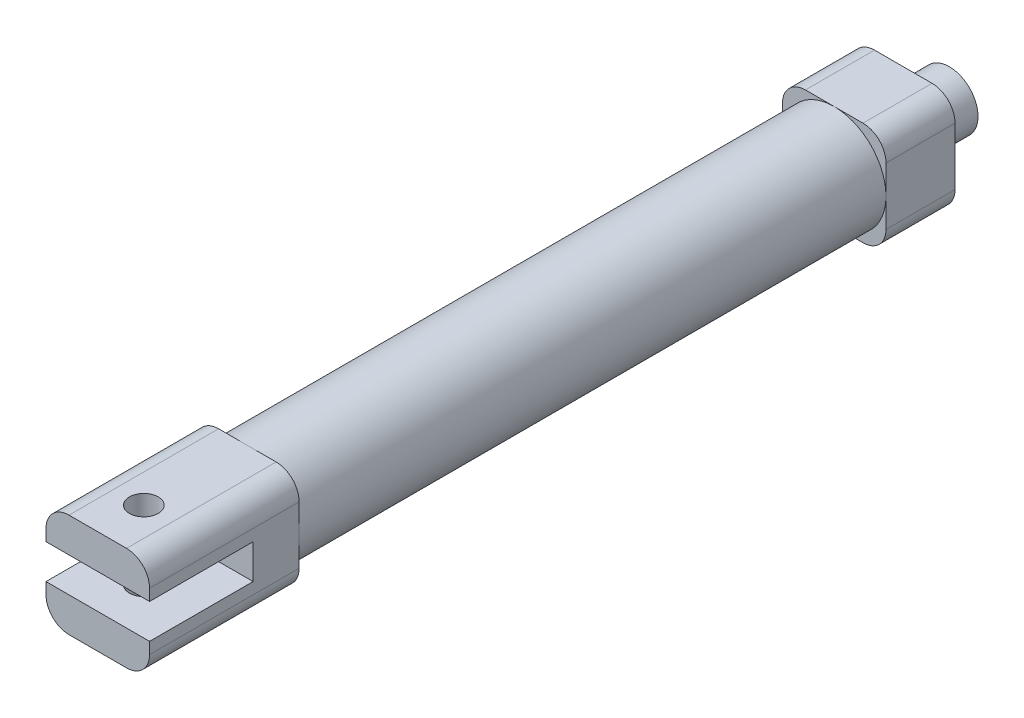
SolidWorks part; units mm, degrees
ref_plane "前视基准面" through (0, 0, 0) normal (0, 0, 1) x (1, 0, 0)
ref_plane "上视基准面" through (0, 0, 0) normal (0, 1, 0) x (1, 0, 0)
ref_plane "右视基准面" through (0, 0, 0) normal (1, 0, 0) x (0, 0, -1)
sketch "草图1" plane through (0, 0, 0) normal (0, 0, 1) x (1, 0, 0)
  circle A0 centre (0, 0) radius 9
  circle A1 centre (0, 0) radius 8
  dimension "D1" = 18
  dimension "D2" = 16
extrude "凸台-拉伸1" add sketch "草图1" along normal blind 102
sketch "草图2" plane through (0, 0, 102) normal (0, 0, 1) x (1, 0, 0)
  line L1 (-5, -9) -> (5, -9)
  line L2 (-9, -5) -> (-9, 5)
  line L3 (-5, 9) -> (5, 9)
  line L4 (9, -5) -> (9, 5)
  line L5 (-9, -9) -> (9, 9) construction
  line L6 (-9, 9) -> (9, -9) construction
  arc A0 (-5, 9) -> (-9, 5) centre (-5, 5) ccw
  arc A1 (9, 5) -> (5, 9) centre (5, 5) ccw
  arc A2 (9, -5) -> (5, -9) centre (5, -5) cw
  arc A3 (-9, -5) -> (-5, -9) centre (-5, -5) ccw
  point P0 (0, 0)
  dimension "D3" = 4
  dimension "D4" = 4
  dimension "D5" = 4
  dimension "D6" = 4
  dimension "D1" = 18
  dimension "D2" = 18
extrude "凸台-拉伸2" add sketch "草图2" along normal blind 26
sketch "草图3" plane through (0, 0, 0) normal (0, 0, -1) x (-1, 0, 0)
  line L1 (-5, -9) -> (5, -9)
  line L2 (-9, -5) -> (-9, 5)
  line L3 (-5, 9) -> (5, 9)
  line L4 (9, -5) -> (9, 5)
  line L5 (-9, -9) -> (9, 9) construction
  line L6 (-9, 9) -> (9, -9) construction
  arc A0 (-9, -5) -> (-5, -9) centre (-5, -5) ccw
  arc A1 (5, -9) -> (9, -5) centre (5, -5) ccw
  arc A2 (9, 5) -> (5, 9) centre (5, 5) ccw
  arc A3 (-5, 9) -> (-9, 5) centre (-5, 5) ccw
  point P0 (0, 0)
  dimension "D3" = 4
  dimension "D1" = 18
  dimension "D2" = 18
extrude "凸台-拉伸3" add sketch "草图3" along normal blind 12
sketch "草图4" plane through (0, 0, -12) normal (0, 0, -1) x (-1, 0, 0)
  circle A0 centre (0, 0) radius 5
extrude "凸台-拉伸4" add sketch "草图4" along normal blind 8
sketch "草图5" plane through (0, 0, -20) normal (0, 0, -1) x (-1, 0, 0)
  circle A0 centre (0, 0) radius 2.5
extrude "切除-拉伸1" cut sketch "草图5" against normal blind 38
sketch "草图6" plane through (-9, 0, 0) normal (-1, 0, 0) x (0, 0, 1)
  line L0 (0, -9) -> (0, 9) construction
  circle A0 centre (-4, 0) radius 2
  circle A1 centre (106, 0) radius 1.9805
  dimension "D1" = 4
  dimension "D2" = 4
extrude "切除-拉伸3" cut sketch "草图6" against normal blind 3
sketch "草图7" plane through (-9, 0, 0) normal (-1, 0, 0) x (0, 0, 1)
  line L0 (128, 5) -> (128, -5) construction
  line L1 (128, 3) -> (110, 3)
  line L2 (128, 3) -> (128, -3)
  line L3 (128, -3) -> (110, -3)
  line L4 (110, 3) -> (110, -3)
  line L5 (128, 5) -> (102, 5) construction
  dimension "D1" = 6
  dimension "D2" = 18
  dimension "D3" = 2
extrude "切除-拉伸4" cut sketch "草图7" against normal blind 20
sketch "草图8" plane through (0, -9, 0) normal (0, -1, 0) x (1, 0, 0)
  line L0 (-5, 128) -> (5, 128) construction
  line L1 (5, 128) -> (5, 102) construction
  circle A0 centre (0, 120) radius 2.5
  point P2 (0, 128)
  dimension "D1" = 8
  dimension "D2" = 5
extrude "切除-拉伸5" cut sketch "草图8" against normal blind 20
